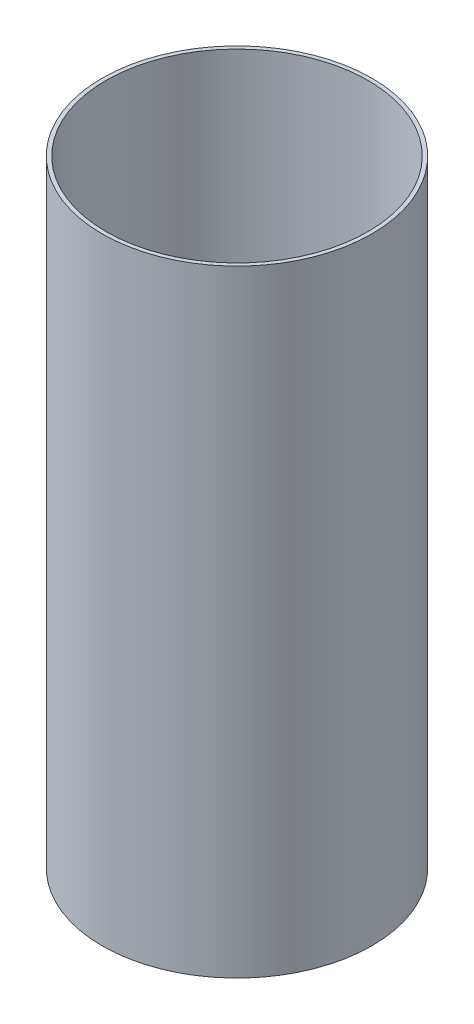
SolidWorks part; units mm, degrees
ref_plane "Front Plane" through (0, 0, 0) normal (0, 0, 1) x (1, 0, 0)
ref_plane "Top Plane" through (0, 0, 0) normal (0, 1, 0) x (1, 0, 0)
ref_plane "Right Plane" through (0, 0, 0) normal (1, 0, 0) x (0, 0, -1)
sketch "Sketch1" plane through (0, 0, 0) normal (0, 1, 0) x (1, 0, 0)
  circle A0 centre (0, 0) radius 17
  circle A1 centre (0, 0) radius 17.5
  dimension "D1" = 35
  dimension "D2" = 0.5
extrude "Boss-Extrude1" add sketch "Sketch1" along normal mid plane 80
